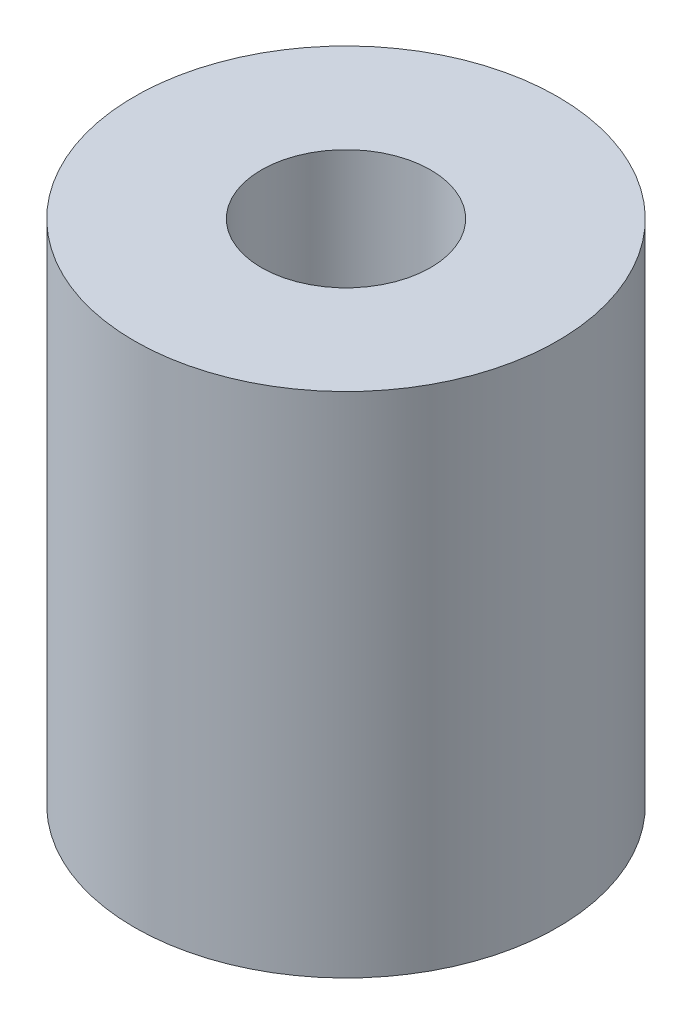
SolidWorks part; units mm, degrees
material "6061 Alloy"
ref_plane "Front Plane" through (0, 0, 0) normal (0, 0, 1) x (1, 0, 0)
ref_plane "Top Plane" through (0, 0, 0) normal (0, 1, 0) x (1, 0, 0)
ref_plane "Right Plane" through (0, 0, 0) normal (1, 0, 0) x (0, 0, -1)
sketch "Sketch1" plane through (0, 0, 0) normal (0, 1, 0) x (1, 0, 0)
  circle A0 centre (0, 0) radius 2.5
  circle A1 centre (0, 0) radius 6.25
extrude "Boss-Extrude1" add sketch "Sketch1" along normal blind 15
